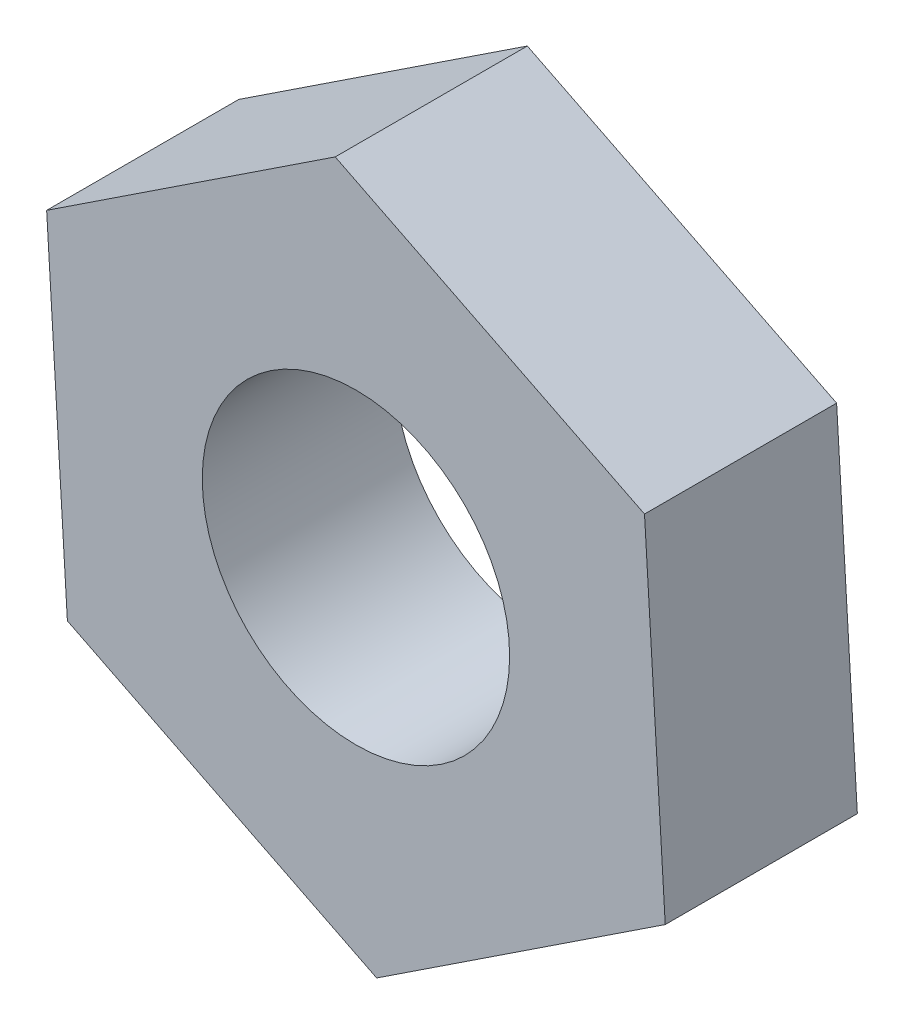
SolidWorks part; units mm, degrees
ref_plane "Front Plane" through (0, 0, 0) normal (0, 0, 1) x (1, 0, 0)
ref_plane "Top Plane" through (0, 0, 0) normal (0, 1, 0) x (1, 0, 0)
ref_plane "Right Plane" through (0, 0, 0) normal (1, 0, 0) x (0, 0, -1)
sketch "Sketch1" plane through (0, 0, 0) normal (0, 0, 1) x (1, 0, 0)
  line L1 (-0.5397, 8.9838) -> (-8.05, 4.0245)
  line L2 (-8.05, 4.0245) -> (-7.5104, -4.9593)
  line L3 (-7.5104, -4.9593) -> (0.5397, -8.9838)
  line L4 (0.5397, -8.9838) -> (8.05, -4.0245)
  line L5 (8.05, -4.0245) -> (7.5104, 4.9593)
  line L6 (7.5104, 4.9593) -> (-0.5397, 8.9838)
  circle A0 centre (0, 0) radius 7.7942 construction
  circle A1 centre (0, 0) radius 4
  dimension "D2" = 8
  dimension "D1" = 9
extrude "Boss-Extrude1" add sketch "Sketch1" along normal blind 5
